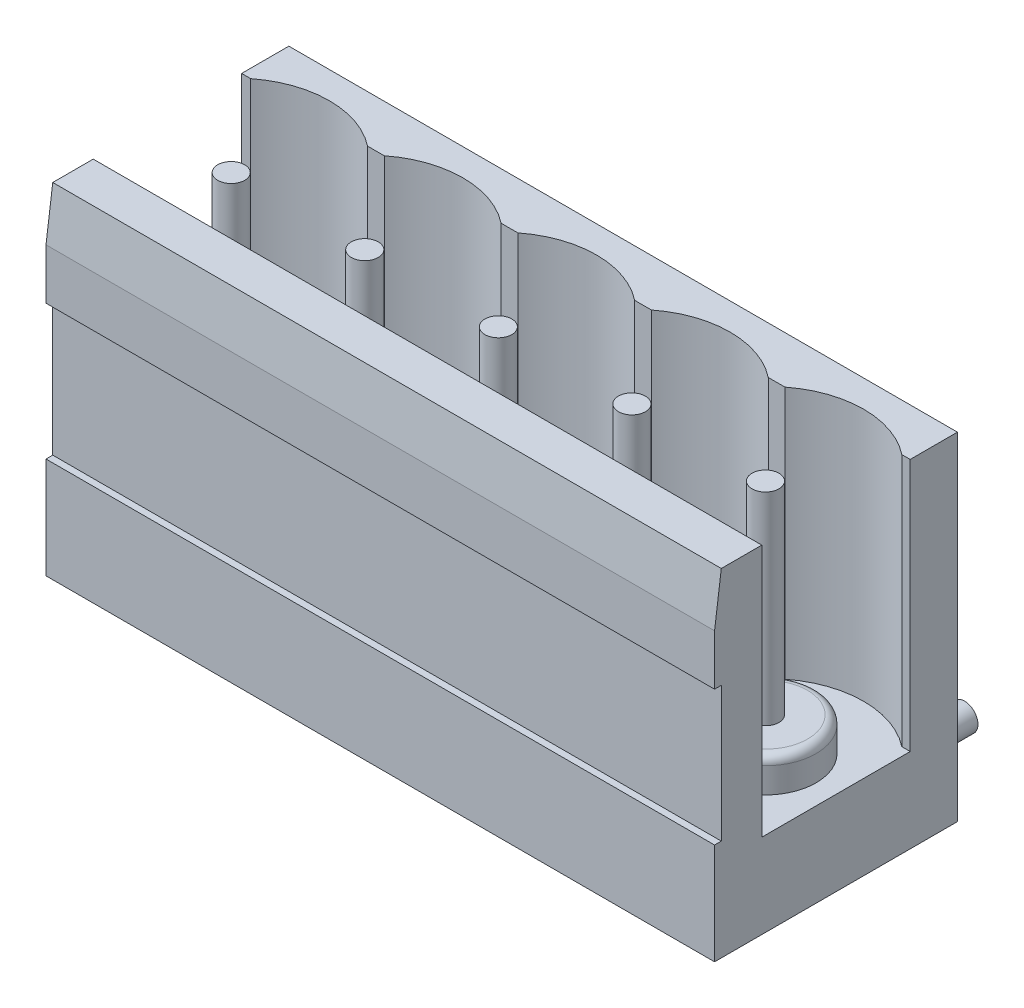
SolidWorks part; units mm, degrees
ref_plane "前视基准面" through (0, 0, 0) normal (0, 0, 1) x (1, 0, 0)
ref_plane "上视基准面" through (0, 0, 0) normal (0, 1, 0) x (1, 0, 0)
ref_plane "右视基准面" through (0, 0, 0) normal (1, 0, 0) x (0, 0, -1)
sketch "草图1" plane through (0, 0, 0) normal (0, 0, 1) x (1, 0, 0)
  line L0 (0, 0) -> (31.5, 0)
  line L1 (31.5, 0) -> (31.5, 10)
  line L2 (31.5, 10) -> (0, 10)
  line L3 (0, 10) -> (0, 0)
  dimension "D1" = 31.5
  dimension "D2" = 10
extrude "凸台-拉伸1" add sketch "草图1" along normal blind 7.2
sketch "草图2" plane through (31.5, 0, 0) normal (1, 0, 0) x (0, 0, -1)
  line L0 (-8.1771, 3) -> (-7, 3)
  line L1 (-7, 3) -> (-7, 7)
  line L2 (-7, 7) -> (-8.1771, 7)
  line L3 (-7.2, 0) -> (0, 0) construction
  line L4 (-7.2, 10) -> (0, 10) construction
  line L5 (-7.2, 0) -> (-7.2, 10) construction
  line L6 (-8.1771, 7) -> (-8.1771, 3)
  point P2 (-3.6, 0)
  dimension "D1" = 3
  dimension "D2" = 3
  dimension "D3" = 0.2
extrude "切除-拉伸1" cut sketch "草图2" against normal through all
sketch "草图3" plane through (31.5, 0, 0) normal (1, 0, 0) x (0, 0, -1)
  line L1 (-7.2, 10) -> (0, 10) construction
  line L2 (-7, 10) -> (-7.2, 8.5)
  line L3 (-7.2, 7) -> (-7.2, 10) construction
  line L4 (-7.2, 8.5) -> (-7.2, 10)
  line L5 (-7.2, 10) -> (-7, 10)
extrude "切除-拉伸2" cut sketch "草图3" against normal through all
sketch "草图6" plane through (0, 10, 0) normal (0, 1, 0) x (1, 0, 0)
  line L0 (0.3918, -1.4) -> (0, -1.4)
  line L6 (31.5, 0) -> (0, 0) construction
  line L8 (0.5, -0.8) -> (31.5, -0.8) construction
  line L9 (31.5, -7) -> (31.5, 0) construction
  line L10 (31.5, -1.4) -> (0.5, -1.4)
  line L11 (0.5, -5.8) -> (31.5, -5.8)
  line L12 (0.3918, -5.8) -> (0.5, -5.8)
  line L13 (0, -7) -> (0, 0) construction
  line L14 (0.3918, -0.8) -> (0.5, -0.8)
  line L15 (0.5, -1.4) -> (0.3918, -1.4)
  line L17 (0, -1.4) -> (-0.2811, -1.4)
  line L18 (-0.2811, -1.4) -> (-0.2811, -5.8)
  line L19 (-0.2811, -5.8) -> (0.3918, -5.8)
  line L20 (31.5, -5.8) -> (31.5, -1.4)
  line M1 (0, 0) -> (0, -7)
  line M3 (31.5, -7) -> (31.5, 0)
  dimension "D4" = 5
  dimension "D2" = 0.8
  dimension "D3" = 1.4
extrude "切除-拉伸4" cut sketch "草图6" against normal blind 7.5 contours L19 L12 L11 L10 L15 L0 M1 M3
sketch "草图7" plane through (0, 10, 0) normal (0, 1, 0) x (1, 0, 0)
  line L0 (0, -7.2) -> (0, 0) construction
  line L1 (0.5, -3.6) -> (12.7215, -3.6) construction
  line L2 (-4.2367, -0.8) -> (33.152, -0.8) construction
  line L3 (31.5, 0) -> (0, 0) construction
  line L4 (0.5, 0.674) -> (0.5, -5.1355) construction
  line L5 (2, -8.0931) -> (2, 2.4837) construction
  line L7 (31.5, -1.4) -> (0, -1.4) construction
  line L8 (0.2679, -1.4) -> (3.7321, -1.4)
  line L10 (27.9879, -1.4) -> (31.4521, -1.4)
  line L11 (24.0279, -1.4) -> (27.4921, -1.4)
  line L12 (20.0679, -1.4) -> (23.5321, -1.4)
  line L13 (16.1079, -1.4) -> (19.5721, -1.4)
  line L14 (12.1479, -1.4) -> (15.6121, -1.4)
  line L15 (8.1879, -1.4) -> (11.6521, -1.4)
  line L16 (4.2279, -1.4) -> (7.6921, -1.4)
  arc A0 (3.7321, -1.4) -> (0.2679, -1.4) centre (2, -3.6) ccw
  arc A1 (7.6921, -1.4) -> (4.2279, -1.4) centre (5.96, -3.6) ccw
  arc A2 (11.6521, -1.4) -> (8.1879, -1.4) centre (9.92, -3.6) ccw
  arc A3 (15.6121, -1.4) -> (12.1479, -1.4) centre (13.88, -3.6) ccw
  arc A4 (19.5721, -1.4) -> (16.1079, -1.4) centre (17.84, -3.6) ccw
  arc A5 (23.5321, -1.4) -> (20.0679, -1.4) centre (21.8, -3.6) ccw
  arc A6 (27.4921, -1.4) -> (24.0279, -1.4) centre (25.76, -3.6) ccw
  arc A7 (31.4521, -1.4) -> (27.9879, -1.4) centre (29.72, -3.6) ccw
  dimension "D1" = 0.8
  dimension "D2" = 0.5
  dimension "D3" = 3.6
  dimension "D4" = 2
extrude "切除-拉伸5" cut sketch "草图7" against normal blind 7.5
sketch "草图8" plane through (0, 0, 0) normal (0, -1, 0) x (1, 0, 0)
  line L0 (0, 4.2) -> (31.5, 4.2) construction
  line L1 (0, 7.2) -> (0, 0) construction
  line L2 (31.5, 7.2) -> (31.5, 0) construction
  line L3 (15.75, 7.2) -> (15.75, 0) construction
  line L4 (0, 7.2) -> (31.5, 7.2) construction
  line L5 (0, 0) -> (31.5, 0) construction
  line L6 (17.73, 4.2) -> (17.73, 0) construction
  line L7 (18.23, 4.2) -> (18.23, 0)
  line L8 (17.23, 4.2) -> (17.23, 0)
  line L9 (17.23, 4.2) -> (18.23, 4.2)
  line L10 (17.23, 0) -> (18.23, 0)
  line L11 (21.19, 4.2) -> (21.19, 0)
  line L12 (22.19, 4.2) -> (22.19, 0)
  line L13 (21.19, 0) -> (22.19, 0)
  line L14 (21.19, 4.2) -> (22.19, 4.2)
  line L15 (25.15, 4.2) -> (25.15, 0)
  line L16 (26.15, 4.2) -> (26.15, 0)
  line L17 (25.15, 0) -> (26.15, 0)
  line L18 (25.15, 4.2) -> (26.15, 4.2)
  line L19 (29.11, 4.2) -> (29.11, 0)
  line L20 (30.11, 4.2) -> (30.11, 0)
  line L21 (29.11, 0) -> (30.11, 0)
  line L22 (29.11, 4.2) -> (30.11, 4.2)
  line L23 (2.39, 4.2) -> (1.39, 4.2)
  line L24 (6.35, 4.2) -> (5.35, 4.2)
  line L25 (10.31, 4.2) -> (9.31, 4.2)
  line L26 (10.31, 0) -> (9.31, 0)
  line L27 (6.35, 0) -> (5.35, 0)
  line L28 (2.39, 0) -> (1.39, 0)
  line L29 (1.39, 4.2) -> (1.39, 0)
  line L30 (2.39, 4.2) -> (2.39, 0)
  line L31 (5.35, 4.2) -> (5.35, 0)
  line L32 (6.35, 4.2) -> (6.35, 0)
  line L33 (9.31, 4.2) -> (9.31, 0)
  line L34 (10.31, 4.2) -> (10.31, 0)
  line L35 (14.27, 4.2) -> (13.27, 4.2)
  line L36 (14.27, 0) -> (13.27, 0)
  line L37 (13.27, 4.2) -> (13.27, 0)
  line L38 (14.27, 4.2) -> (14.27, 0)
  dimension "D1" = 3
  dimension "D2" = 1.98
  dimension "D3" = 1
  dimension "D4" = 4
extrude "切除-拉伸6" cut sketch "草图8" against normal blind 1
sketch "草图9" plane through (0, 0, 4.2) normal (0, 0, -1) x (-1, 0, 0)
  line L0 (-1.39, 0) -> (-2.39, 0) construction
  line L1 (-2.39, 0) -> (-2.39, 1) construction
  line L2 (-2.39, 1) -> (-1.39, 1) construction
  line L3 (-1.39, 1) -> (-1.39, 0) construction
  line L4 (-1.39, 0) -> (-2.39, 1) construction
  line L5 (-2.39, 0) -> (-1.39, 1) construction
  circle A0 centre (-1.89, 0.5) radius 0.4
  circle A1 centre (-5.85, 0.5) radius 0.4
  circle A2 centre (-9.81, 0.5) radius 0.4
  circle A3 centre (-13.77, 0.5) radius 0.4
  circle A4 centre (-17.73, 0.5) radius 0.4
  circle A5 centre (-21.69, 0.5) radius 0.4
  circle A6 centre (-25.65, 0.5) radius 0.4
  circle A7 centre (-29.61, 0.5) radius 0.4
  dimension "D1" = 0.8
extrude "凸台-拉伸5" add sketch "草图9" along normal blind 6.5
sketch "草图10" plane through (0, 2.5, 0) normal (0, 1, 0) x (1, 0, 0)
  line L0 (0, -7.2) -> (0, 0) construction
  line L1 (1.1289, -3.6) -> (-2.9434, -3.6) construction
  line L2 (15.75, -5.8) -> (15.75, 3.6831) construction
  circle A0 centre (13.77, -3.6) radius 0.4
  circle A1 centre (9.81, -3.6) radius 0.4
  circle A2 centre (5.85, -3.6) radius 0.4
  circle A3 centre (1.89, -3.6) radius 0.4
  circle A4 centre (29.61, -3.6) radius 0.4
  circle A5 centre (25.65, -3.6) radius 0.4
  circle A6 centre (21.69, -3.6) radius 0.4
  circle A7 centre (17.73, -3.6) radius 0.4
  dimension "D1" = 0.8
  dimension "D2" = 3.96
  dimension "D3" = 15.75
  dimension "D4" = 4
extrude "凸台-拉伸6" add sketch "草图10" along normal blind 7
sketch "草图11" plane through (0, 2.5, 0) normal (0, 1, 0) x (1, 0, 0)
  circle A0 centre (29.61, -3.6) radius 1.5
  circle A1 centre (25.65, -3.6) radius 1.5
  circle A2 centre (21.69, -3.6) radius 1.5
  circle A3 centre (17.73, -3.6) radius 1.5
  circle A4 centre (13.77, -3.6) radius 1.5
  circle A5 centre (9.81, -3.6) radius 1.5
  circle A6 centre (5.85, -3.6) radius 1.5
  circle A7 centre (1.89, -3.6) radius 1.5
extrude "凸台-拉伸7" add sketch "草图11" along normal blind 1
fillet "圆角1" radius 0.25 8 edges at (1.89, 3.5, 5.1) (5.85, 3.5, 5.1) (9.81, 3.5, 5.1) (13.77, 3.5, 5.1) (17.73, 3.5, 5.1) (21.69, 3.5, 5.1) (25.65, 3.5, 5.1) (29.61, 3.5, 5.1)
sketch "草图12" plane through (0, 10, 0) normal (0, 1, 0) x (-1, 0, 0)
  line L0 (-19.82, 1.4) -> (-19.82, 0) construction
  line L1 (-20.0679, 1.4) -> (-19.5721, 1.4) construction
  line L2 (-31.5, 0) -> (0, 0) construction
sketch "草图13" plane through (0, 10, 0) normal (0, 1, 0) x (1, 0, 0)
  line L0 (19.82, 0) -> (19.82, -8.0617)
  line L1 (19.82, -8.0617) -> (32.0188, -8.0617)
  line L2 (32.0188, -8.0617) -> (32.0188, 2.7533)
  line L3 (32.0188, 2.7533) -> (19.82, 2.7533)
  line L4 (19.82, 2.7533) -> (19.82, 0)
extrude "切除-拉伸7" cut sketch "草图13" against normal through all
